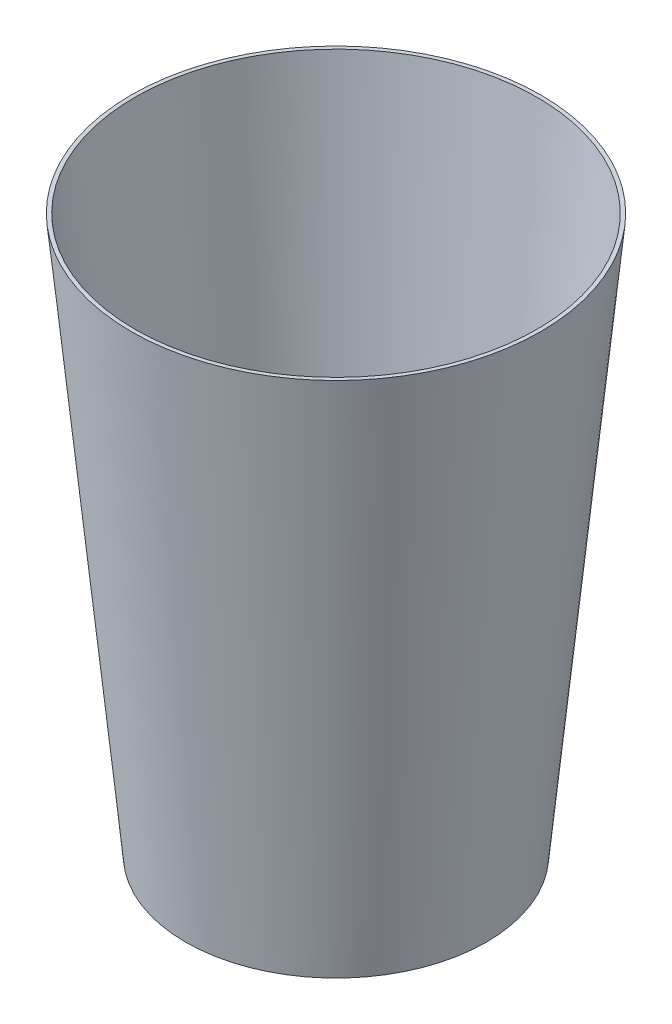
SolidWorks part; units mm, degrees
ref_plane "Front Plane" through (0, 0, 0) normal (0, 0, 1) x (1, 0, 0)
ref_plane "Top Plane" through (0, 0, 0) normal (0, 1, 0) x (1, 0, 0)
ref_plane "Right Plane" through (0, 0, 0) normal (1, 0, 0) x (0, 0, -1)
sketch "Sketch1" plane through (0, 0, 0) normal (0, 1, 0) x (1, 0, 0)
  circle A0 centre (0, 0) radius 35
extrude "Boss-Extrude1" add sketch "Sketch1" against normal blind 95 draft 5.588
sketch "Sketch3" plane through (0, 0, 0) normal (0, 1, 0) x (1, 0, 0)
  circle A0 centre (0, 0) radius 34.35
extrude "Cut-Extrude1" cut sketch "Sketch3" against normal offset from surface 0.65 draft 5.588
